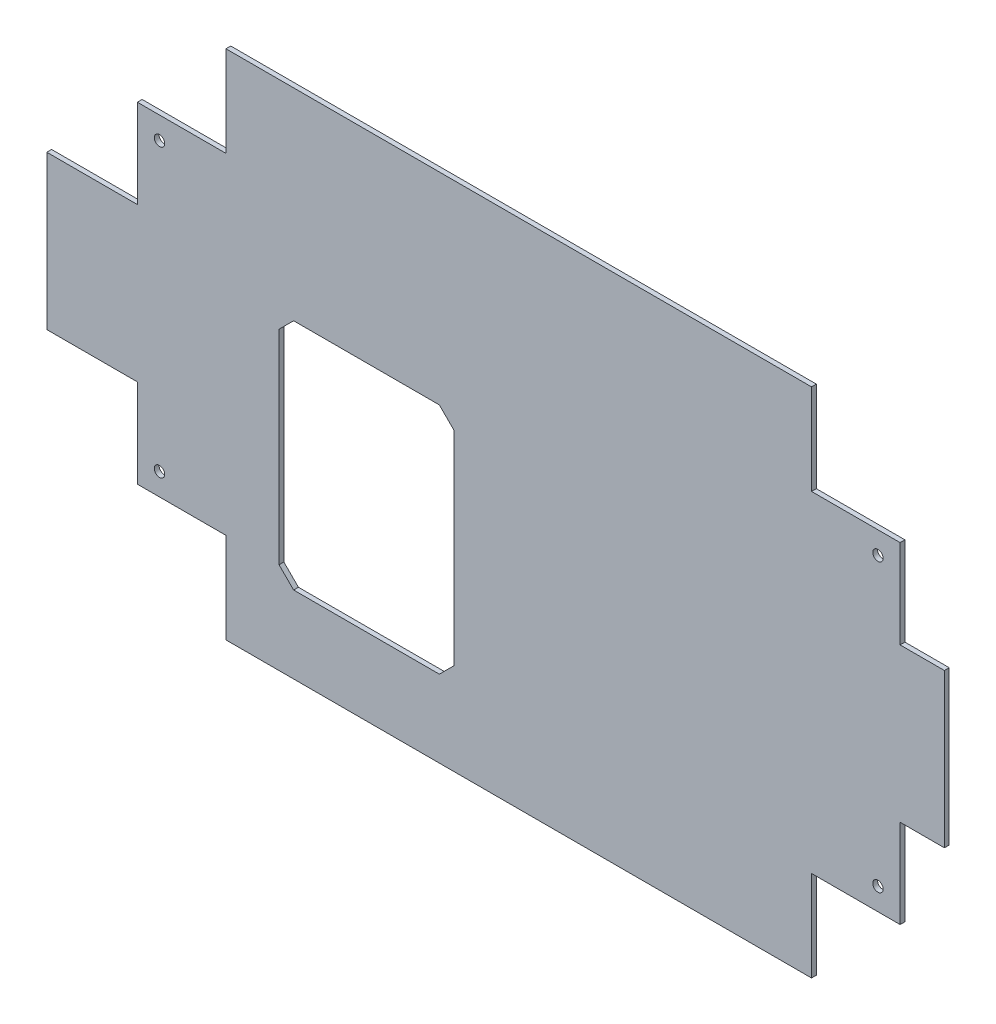
SolidWorks part; units mm, degrees
ref_plane "Plan de face" through (0, 0, 0) normal (0, 0, 1) x (1, 0, 0)
ref_plane "Plan de dessus" through (0, 0, 0) normal (0, 1, 0) x (1, 0, 0)
ref_plane "Plan de droite" through (0, 0, 0) normal (1, 0, 0) x (0, 0, -1)
sketch "Esquisse1" plane through (0, 0, 0) normal (0, 0, 1) x (1, 0, 0)
  line L0 (-615.95, 52.7) -> (-615.95, -52.7)
  line L1 (-615.95, -52.7) -> (-553.8, -52.7)
  line L2 (-553.8, -52.7) -> (-553.8, -113.5)
  line L3 (-553.8, -113.5) -> (-493, -113.5)
  line L4 (-493, -113.5) -> (-493, -174.3)
  line L5 (-493, -174.3) -> (-91.2, -174.3)
  line L6 (-91.2, -174.3) -> (-91.2, -113.5)
  line L7 (-91.2, -113.5) -> (-30.4, -113.5)
  line L8 (-30.4, -113.5) -> (-30.4, -52.7)
  line L9 (-30.4, -52.7) -> (0, -52.7)
  line L10 (0, -52.7) -> (0, 52.7)
  line L11 (0, 52.7) -> (-30.4, 52.7)
  line L12 (-30.4, 52.7) -> (-30.4, 113.5)
  line L13 (-30.4, 113.5) -> (-91.2, 113.5)
  line L14 (-91.2, 113.5) -> (-91.2, 182)
  line L15 (-615.95, 52.7) -> (-553.8, 52.7)
  line L16 (-553.8, 52.7) -> (-553.8, 113.5)
  line L17 (-553.8, 113.5) -> (-493, 113.5)
  line L18 (-493, 113.5) -> (-493, 182)
  line L19 (-493, 182) -> (-91.2, 182)
  point P28 (0, 0)
  dimension "D1" = 105.4
  dimension "D2" = 401.8
  dimension "D3" = 60.8
  dimension "D4" = 30.4
  dimension "D5" = 60.8
  dimension "D6" = 68.5
  dimension "D7" = 60.8
  dimension "D8" = 60.8
  dimension "D9" = 62.15
extrude "Boss.-Extru.1" add sketch "Esquisse1" along normal blind 3.3
sketch "Esquisse2" plane through (0, 0, 3.3) normal (0, 0, 1) x (1, 0, 0)
  line L0 (-91.2, 113.5) -> (-91.2, 182) construction
  line L1 (-493, 182) -> (-91.2, 182)
  line L2 (-493, 182) -> (-493, 175.65)
  line L3 (-493, 175.65) -> (-91.2, 175.65)
  line L4 (-91.2, 182) -> (-91.2, 175.65)
  line L5 (-493, 182) -> (-91.2, 175.65) construction
  line L6 (-493, 175.65) -> (-91.2, 182) construction
  line L7 (-91.2, 182) -> (-493, 182) construction
  line L8 (-493, 182) -> (-493, 113.5) construction
  point P4 (-292.1, 178.825)
  dimension "D1" = 6.35
extrude "Enlèv. mat.-Extru.1" cut sketch "Esquisse2" against normal through all
hole_wizard "Dégagement 1/41" positions "Esquisse3" profile "Esquisse4" hole size "1/4" standard "Ansi Inch" end condition through all
sketch "Esquisse3" plane through (0, 0, 0) normal (0, 0, -1) x (-1, 0, 0)
  point P0 (45.6, 98.3)
  point P2 (45.6, -98.3)
  point P4 (538.6, -98.3)
  point P6 (538.6, 98.3)
sketch "Esquisse4" plane through (-45.6, 98.3, 0) normal (1, 0, 0) x (0, 1, 0)
  line L0 (0, 0) -> (0, 3.3)
  line L1 (0, 3.3) -> (3.5712, 3.3)
  line L2 (3.5712, 3.3) -> (3.5712, 0)
  line L5 (3.5712, 0) -> (0, 0)
  line L11 (0, -6.35) -> (0, 107.95) construction
  dimension "Diamètre du perçage jusqu'au prochain" = 7.1425
  dimension "Profondeur du perçage jusqu'au prochain" = 3.3
sketch "Esquisse5" plane through (0, 0, 3.3) normal (0, 0, 1) x (1, 0, 0)
  line L0 (-91.2, -174.3) -> (-91.2, -113.5) construction
  line L1 (-493, -174.3) -> (-91.2, -174.3)
  line L2 (-493, -174.3) -> (-493, -175.65)
  line L3 (-493, -175.65) -> (-91.2, -175.65)
  line L4 (-91.2, -174.3) -> (-91.2, -175.65)
  line L5 (-493, -174.3) -> (-91.2, -175.65) construction
  line L6 (-493, -175.65) -> (-91.2, -174.3) construction
  point P4 (-292.1, -174.975)
  dimension "D1" = 1.35
extrude "Boss.-Extru.2" add sketch "Esquisse5" against normal through all
mirror "Symétrie1" [suppressed]
delete or keep bodies "Corps-Supprimer/Garder 1" [suppressed] type delete bodies bodies 105
sketch "Esquisse6" plane through (0, 0, 0) normal (0, 0, -1) x (-1, 0, 0)
  line L0 (336.5665, -122.7684) -> (456.5665, -122.7684)
  line L1 (456.5665, -122.7684) -> (456.5665, 37.2316)
  line L2 (456.5665, 37.2316) -> (336.5665, 37.2316)
  line L3 (336.5665, 37.2316) -> (336.5665, -122.7684)
  line L4 (396.5665, 37.2316) -> (396.5665, -122.7684) construction
  line L5 (456.5665, -42.7684) -> (336.5665, -42.7684) construction
  point P8 (396.5665, -42.7684)
  point P9 (0, 0)
  dimension "D1" = 120
  dimension "D2" = 160
  dimension "D3" = 396.5665
  dimension "D4" = 42.7684
extrude "Enlèv. mat.-Extru.2" cut sketch "Esquisse6" against normal through all
chamfer "Chanfrein1" distance 10 angle 45 4 edges at (-336.5665, -122.7684, 1.65) (-456.5665, -122.7684, 1.65) (-456.5665, 37.2316, 1.65) (-336.5665, 37.2316, 1.65)
